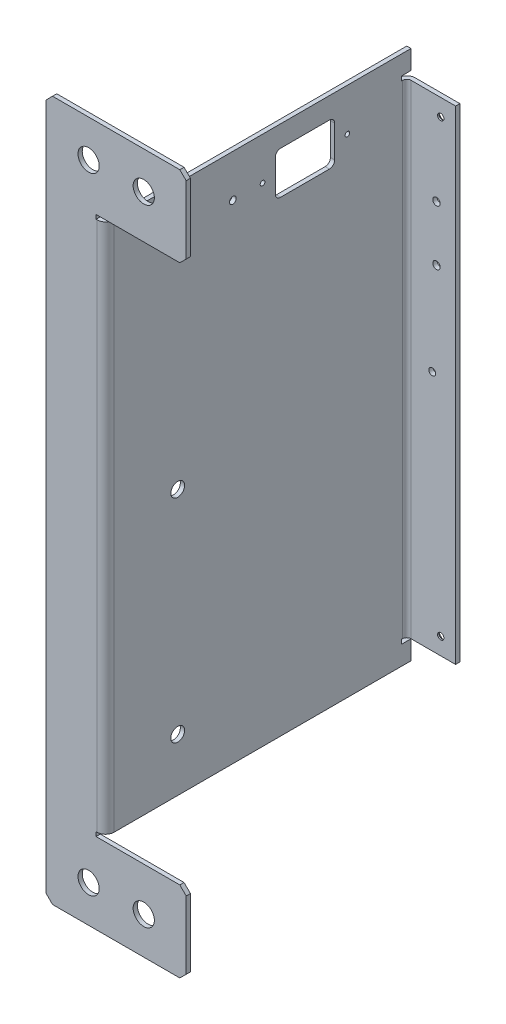
SolidWorks part; units mm, degrees
ref_plane "Спереди" through (0, 0, 0) normal (0, 0, 1) x (1, 0, 0)
ref_plane "Сверху" through (0, 0, 0) normal (0, 1, 0) x (1, 0, 0)
ref_plane "Справа" through (0, 0, 0) normal (1, 0, 0) x (0, 0, -1)
sketch "Эскиз1" plane through (0, 0, 0) normal (0, 0, 1) x (1, 0, 0)
  line L0 (-43.6006, 0) -> (53.6851, 0) construction
  line L1 (-15.3894, -165) -> (44.6106, -165)
  line L2 (-18.3894, -162) -> (-18.3894, 162)
  line L3 (-15.3894, 165) -> (44.6106, 165)
  line L4 (47.6106, -162) -> (47.6106, -130)
  line L5 (47.6106, 130) -> (47.6106, 162)
  line L6 (44.6106, -127) -> (9.6106, -127)
  line L7 (-37.9272, -147.5) -> (69.1915, -147.5) construction
  line L8 (44.6106, 127) -> (9.6106, 127)
  line L9 (9.6106, -127) -> (9.6106, 127)
  line L10 (-43.6006, 147.5) -> (58.9409, 147.5) construction
  line L11 (-18.3894, 162) -> (-15.3894, 165)
  line L12 (44.6106, 165) -> (47.6106, 162)
  line L13 (44.6106, 127) -> (47.6106, 130)
  line L14 (47.6106, -130) -> (44.6106, -127)
  line L15 (44.6106, -165) -> (47.6106, -162)
  line L16 (-18.3894, -162) -> (-15.3894, -165)
  circle A0 centre (1.6106, -147.5) radius 5
  circle A1 centre (27.6106, -147.5) radius 5
  circle A2 centre (27.6106, 147.5) radius 5
  circle A3 centre (1.6106, 147.5) radius 5
  point P0 (-18.3894, -165)
  point P1 (47.6106, 165)
  point P2 (-18.3894, 165)
  point P3 (47.6106, -165)
  point P6 (47.6106, -127)
  point P8 (47.6106, 127)
  dimension "D6" = 20
  dimension "D7" = 26
  dimension "D8" = 10
  dimension "D1" = 330
  dimension "D2" = 66
  dimension "D3" = 38
  dimension "D4" = 295
  dimension "D5" = 35
  dimension "D9" = 28
  dimension "D12" = 3
  dimension "D13" = 3
  dimension "D14" = 3
  dimension "D15" = 3
  dimension "D16" = 3
  dimension "D17" = 3
extrude "Вытянуть1" add sketch "Эскиз1" along normal blind 2
sketch "Эскиз2" plane through (0, 0, 2) normal (0, 0, 1) x (1, 0, 0)
  line L0 (-77.0675, 0) -> (63.9758, 0) construction
  line L1 (9.6106, -127) -> (9.6106, 127) construction
  line L2 (9.6106, -125) -> (7.6106, -125)
  line L3 (9.6106, -125) -> (9.6106, 125)
  line L4 (9.6106, 125) -> (7.6106, 125)
  line L5 (7.6106, -125) -> (7.6106, 125)
  dimension "D1" = 2
  dimension "D2" = 250
extrude "Вытянуть2" add sketch "Эскиз2" against normal blind 144
sketch "Эскиз3" plane through (9.6106, 0, 0) normal (1, 0, 0) x (0, 0, -1)
  line L0 (-20.1669, 0) -> (172.2564, 0) construction
  line L1 (142, -125) -> (142, 125) construction
  line L2 (140, -114) -> (142, -114)
  line L3 (140, -114) -> (140, 114)
  line L4 (140, 114) -> (142, 114)
  line L5 (142, -114) -> (142, 114)
  dimension "D1" = 2
  dimension "D2" = 228
extrude "Вытянуть3" add sketch "Эскиз3" along normal blind 23
sketch "Эскиз4" plane through (0, 0, 2) normal (0, 0, 1) x (1, 0, 0)
  line L0 (-8.6712, 0) -> (62.9395, 0) construction
  line L1 (9.6106, 127) -> (5.1106, 127)
  line L2 (9.6106, 127) -> (9.6106, 125)
  line L3 (9.6106, 125) -> (5.1106, 125)
  line L4 (5.1106, 127) -> (5.1106, 125)
  line L5 (9.6106, 127) -> (44.6106, 127) construction
  line L6 (9.6106, -125) -> (5.1106, -125)
  line L7 (9.6106, -127) -> (9.6106, -125)
  line L8 (9.6106, -127) -> (5.1106, -127)
  line L9 (5.1106, -127) -> (5.1106, -125)
  dimension "D1" = 4.5
  dimension "D2" = 2
extrude "Вырез-Вытянуть1" cut sketch "Эскиз4" against normal blind 2
sketch "Эскиз5" plane through (9.6106, 0, 0) normal (1, 0, 0) x (0, 0, -1)
  line L0 (-17.691, 0) -> (90.0382, 0) construction
  line L1 (142, -114) -> (137.5, -114)
  line L2 (142, -114) -> (142, -116)
  line L3 (142, -116) -> (137.5, -116)
  line L4 (137.5, -114) -> (137.5, -116)
  line L5 (142, 116) -> (137.5, 116)
  line L6 (142, 114) -> (142, 116)
  line L7 (142, 114) -> (137.5, 114)
  line L8 (137.5, 114) -> (137.5, 116)
  dimension "D1" = 2
  dimension "D2" = 4.5
extrude "Вырез-Вытянуть2" cut sketch "Эскиз5" against normal blind 2
fillet "Скругление3" radius 2
fillet "Скругление4" radius 4
sketch "Эскиз6" plane through (0, 0, -142) normal (0, 0, -1) x (-1, 0, 0)
  line L0 (0, 0) -> (-64.9274, 0) construction
  line L1 (-32.6106, -114) -> (-32.6106, 114) construction
  line L2 (-32.6106, -114) -> (-11.6106, -114) construction
  line L6 (-32.6106, 114) -> (-11.6106, 114) construction
  circle A0 centre (-21.6106, 0) radius 1.6
  circle A1 centre (-25.6106, -106) radius 1.5
  circle A2 centre (-25.6106, 106) radius 1.5
  circle A3 centre (-23.6106, 44.5) radius 1.75
  circle A4 centre (-23.6106, 70.5) radius 1.75
  dimension "D1" = 11
  dimension "D2" = 3.2
  dimension "D3" = 7
  dimension "D4" = 8
  dimension "D5" = 3
  dimension "D6" = 26
  dimension "D8" = 3.5
  dimension "D9" = 3.5
  dimension "D7" = 43.5
  dimension "D10" = 9
  dimension "D11" = 9
extrude "Вырез-Вытянуть3" cut sketch "Эскиз6" against normal blind 2
cosmetic thread "Условное изображение резьбы1" parameters "D1"=2, "D2"=4
chamfer "Фаска1" distance 1.3 angle 45
sketch "Эскиз8" plane through (9.6106, 0, 0) normal (1, 0, 0) x (0, 0, -1)
  line L0 (-42.5242, 0) -> (111.0097, 0) construction
  line L1 (140, 0) -> (142, 0) construction
  line L2 (-2, -162) -> (-2, -130) construction
  line L3 (32, 99.2174) -> (32, -101.1338) construction
  line L4 (45.9471, -105) -> (118.5831, -105) construction
  line L5 (92, 91.0392) -> (92, 121.8979) construction
  line L6 (142, 125) -> (2, 125) construction
  line L7 (142, -125) -> (2, -125) construction
  line L8 (92, -79.373) -> (92, -135.8433) construction
  line L9 (142, -114) -> (142, 114) construction
  line L11 (142, -114) -> (142, 114) construction
  line L12 (80.5, 95) -> (103.5, 95)
  line L19 (106, 112.5) -> (106, 97.5)
  line L20 (80.5, 115) -> (103.5, 115)
  line L21 (78, 112.5) -> (78, 97.5)
  circle A0 centre (32, 0) radius 3.25
  circle A1 centre (32, -100) radius 3.25
  circle A2 centre (32, 100) radius 3.25
  arc A3 (80.5, 115) -> (78, 112.5) centre (80.5, 112.5) ccw
  arc A4 (106, 112.5) -> (103.5, 115) centre (103.5, 112.5) ccw
  arc A5 (80.5, 95) -> (78, 97.5) centre (80.5, 97.5) cw
  arc A6 (103.5, 95) -> (106, 97.5) centre (103.5, 97.5) ccw
  circle A12 centre (112, 105) radius 1.1
  circle A19 centre (72, 105) radius 1.1
  circle A20 centre (58, 105) radius 1.6
  dimension "D1" = 6.5
  dimension "D3" = 100
  dimension "D5" = 20
  dimension "D6" = 2.5
  dimension "D8" = 26
  dimension "D9" = 28
  dimension "D15" = 40
  dimension "D16" = 20
  dimension "D10" = 10
  dimension "D12" = 2.5
  dimension "D2" = 34
  dimension "D4" = 20
  dimension "D7" = 50
  dimension "D14" = 20
  dimension "D18" = 50
extrude "Вырез-Вытянуть4" cut sketch "Эскиз8" against normal blind 2
cosmetic thread "Условное изображение резьбы2" parameters "D1"=2, "D2"=3
cosmetic thread "Условное изображение резьбы3" parameters "D1"=2, "D2"=3
cosmetic thread "Условное изображение резьбы4" parameters "D1"=2, "D2"=4
cosmetic thread "Условное изображение резьбы5" parameters "D1"=2, "D2"=4
cosmetic thread "Условное изображение резьбы6" parameters "D1"=2, "D2"=3
cosmetic thread "Условное изображение резьбы7" parameters "D1"=2, "D2"=3
